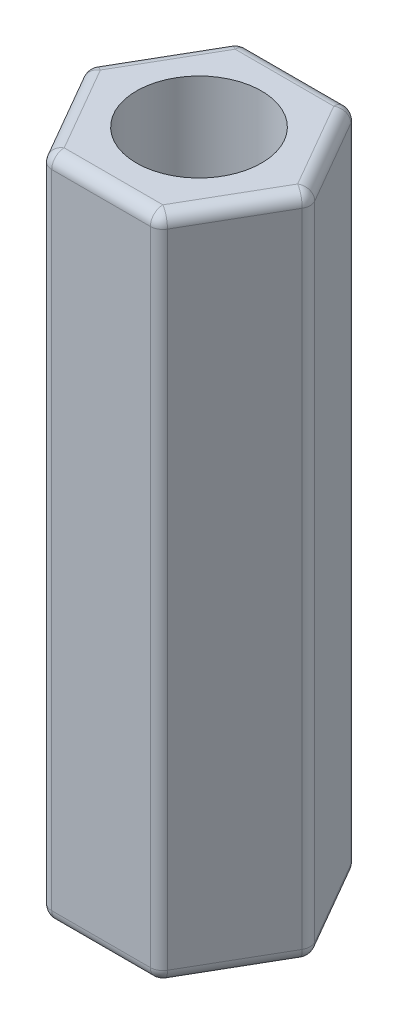
SolidWorks part; units mm, degrees
ref_plane "前视基准面" through (0, 0, 0) normal (0, 0, 1) x (1, 0, 0)
ref_plane "上视基准面" through (0, 0, 0) normal (0, 1, 0) x (1, 0, 0)
ref_plane "右视基准面" through (0, 0, 0) normal (1, 0, 0) x (0, 0, -1)
sketch "草图1" plane through (0, 0, 0) normal (0, 1, 0) x (1, 0, 0)
  line L1 (2.7135, 0) -> (1.3568, 2.35)
  line L2 (1.3568, 2.35) -> (-1.3568, 2.35)
  line L3 (-1.3568, 2.35) -> (-2.7135, 0)
  line L4 (-2.7135, 0) -> (-1.3568, -2.35)
  line L5 (-1.3568, -2.35) -> (1.3568, -2.35)
  line L6 (1.3568, -2.35) -> (2.7135, 0)
  circle A0 centre (0, 0) radius 2.35 construction
  circle A1 centre (0, 0) radius 1.5
  dimension "D1" = 4.7
extrude "凸台-拉伸1" add sketch "草图1" along normal blind 16
fillet "圆角1" radius 0.3 18 edges at (2.7135, 8, 0) (1.3568, 8, -2.35) (-1.3568, 8, -2.35) (-2.7135, 8, 0) (-1.3568, 8, 2.35) (1.3568, 8, 2.35) (0, 16, 2.35) (-2.0352, 16, 1.175) (-2.0352, 16, -1.175) (0, 16, -2.35) (2.0352, 16, -1.175) (2.0352, 16, 1.175) (0, 0, 2.35) (-2.0352, 0, 1.175) (-2.0352, 0, -1.175) (0, 0, -2.35) (2.0352, 0, -1.175) (2.0352, 0, 1.175)
